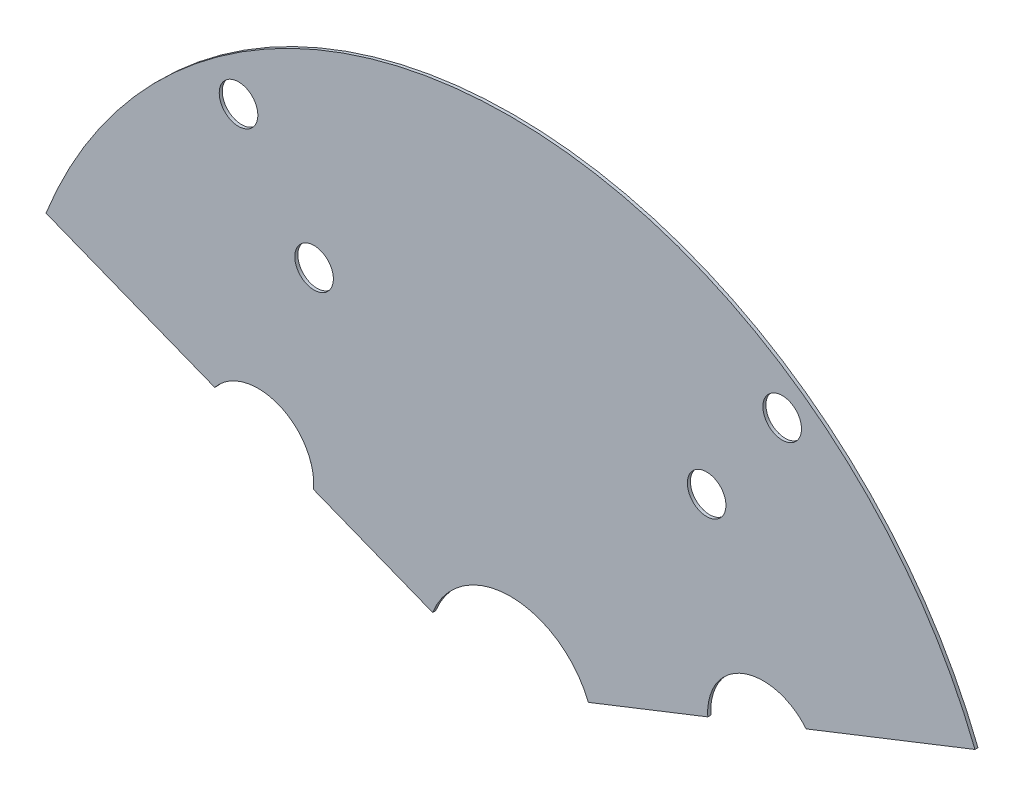
SolidWorks part; units mm, degrees
ref_plane "Front Plane" through (0, 0, 0) normal (0, 0, 1) x (1, 0, 0)
ref_plane "Top Plane" through (0, 0, 0) normal (0, 1, 0) x (1, 0, 0)
ref_plane "Right Plane" through (0, 0, 0) normal (1, 0, 0) x (0, 0, -1)
sketch "Sketch1" plane through (0, 0, 0) normal (0, 0, 1) x (1, 0, 0)
  line L0 (-25.2075, 29.5777) -> (-20.3405, 33.1137)
  line L1 (-22.774, 31.3457) -> (0, 0) construction
  line L2 (0, 0) -> (-50.8, 0) construction
  circle A0 centre (0, 0) radius 50.8
  circle A1 centre (0, 0) radius 38.862 construction
  circle A12 centre (0, 0) radius 19.05 construction
  circle A19 centre (-38.862, 0) radius 9.1764
  circle A20 centre (0, 0) radius 9.7536
  circle A22 centre (-31.44, 22.8425) radius 9.1764
  circle A23 centre (-12.009, 36.96) radius 9.1764
  circle A24 centre (12.009, 36.96) radius 9.1764
  circle A25 centre (31.44, 22.8425) radius 9.1764
  circle A26 centre (38.862, 0) radius 9.1764
  circle A27 centre (31.44, -22.8425) radius 9.1764
  circle A28 centre (12.009, -36.96) radius 9.1764
  circle A29 centre (-12.009, -36.96) radius 9.1764
  circle A30 centre (-31.44, -22.8425) radius 9.1764
  circle A31 centre (-11.1973, 15.4118) radius 9.2964
  circle A32 centre (11.1973, 15.4118) radius 9.2964
  circle A33 centre (18.1176, -5.8868) radius 9.2964
  circle A34 centre (0, -19.05) radius 9.2964
  circle A35 centre (-18.1176, -5.8868) radius 9.2964
  point P27 (0, 0)
  point P32 (0, 0)
  point P43 (0, 0)
  point P49 (0, 0)
  dimension "D1" = 101.6
  dimension "D2" = 11.938
  dimension "D3" = 18.5928
  dimension "D4" = 38.1
  dimension "D5" = 10
  dimension "D6" = 5
sketch "Sketch2" plane through (0, 0, 0) normal (0, 0, 1) x (1, 0, 0)
  circle A0 centre (0, 0) radius 50.165
  circle A1 centre (0, -19.05) radius 9.2964 construction
  circle A2 centre (18.1176, -5.8868) radius 9.2964 construction
  circle A3 centre (11.1973, 15.4118) radius 9.2964 construction
  circle A4 centre (-11.1973, 15.4118) radius 9.2964 construction
  circle A5 centre (-18.1176, -5.8868) radius 9.2964 construction
  circle A6 centre (-38.862, 0) radius 9.1764 construction
  circle A7 centre (-31.44, -22.8425) radius 9.1764 construction
  circle A8 centre (-12.009, -36.96) radius 9.1764 construction
  circle A9 centre (12.009, -36.96) radius 9.1764 construction
  circle A10 centre (31.44, -22.8425) radius 9.1764 construction
  circle A11 centre (38.862, 0) radius 9.1764 construction
  circle A12 centre (31.44, 22.8425) radius 9.1764 construction
  circle A13 centre (12.009, 36.96) radius 9.1764 construction
  circle A14 centre (-12.009, 36.96) radius 9.1764 construction
  circle A15 centre (-31.44, 22.8425) radius 9.1764 construction
  circle A17 centre (0, 0) radius 7.62
  circle A18 centre (0, -19.05) radius 9.2964
  circle A19 centre (18.1176, -5.8868) radius 9.2964
  circle A20 centre (11.1973, 15.4118) radius 9.2964
  circle A21 centre (-11.1973, 15.4118) radius 9.2964
  circle A22 centre (-18.1176, -5.8868) radius 9.2964
  circle A23 centre (-38.862, 0) radius 9.1764
  circle A24 centre (-31.44, -22.8425) radius 9.1764
  circle A25 centre (-12.009, -36.96) radius 9.1764
  circle A26 centre (12.009, -36.96) radius 9.1764
  circle A27 centre (31.44, -22.8425) radius 9.1764
  circle A28 centre (38.862, 0) radius 9.1764
  circle A29 centre (31.44, 22.8425) radius 9.1764
  circle A30 centre (12.009, 36.96) radius 9.1764
  circle A31 centre (-12.009, 36.96) radius 9.1764
  circle A32 centre (-31.44, 22.8425) radius 9.1764
  dimension "D1" = 15.24
  dimension "D2" = 100.33
sketch "Sketch4" plane through (0, 0, 0) normal (0, 0, 1) x (1, 0, 0)
  line L0 (-38.862, 0) -> (-31.44, 22.8425) construction
  line L1 (-11.1973, 15.4118) -> (-18.1176, -5.8868) construction
  line L3 (-2.8326, 36.96) -> (0, 36.96) construction
  line L4 (0, 15.4118) -> (-1.9009, 15.4118) construction
  line L8 (0, 0) -> (0, 50.165) construction
  line L10 (-0.5081, 8.2393) -> (-3.0331, 49.1826)
  line L13 (-28.9637, 39.8651) -> (0, 0) construction
  line L14 (-7.6791, 3.0294) -> (-45.8381, 18.0829)
  arc A3 (-3.0331, 49.1826) -> (-45.8381, 18.0829) centre (0, 0) ccw
  circle A6 centre (-11.1973, 15.4118) radius 9.2964 construction
  circle A7 centre (-12.009, 36.96) radius 9.1764 construction
  circle A8 centre (-31.44, 22.8425) radius 9.1764 construction
  circle A13 centre (-11.1973, 15.4118) radius 9.2964 construction
  circle A14 centre (-12.009, 36.96) radius 9.1764 construction
  circle A15 centre (-31.44, 22.8425) radius 9.1764 construction
  arc A16 (-0.5081, 8.2393) -> (-7.6791, 3.0294) centre (0, 0) ccw
  circle A18 centre (0, 0) radius 50.165 construction
  point P5 (-0.9505, 15.4118)
  point P6 (-1.4163, 36.96)
  dimension "D1" = 8.255
  dimension "D2" = 49.276
  dimension "D3" = 15.4118
  dimension "D4" = 36.96
  dimension "D5" = 28.9637
  dimension "D6" = 39.8651
sketch "Sketch5" plane through (0, 0, 0) normal (0, 0, 1) x (1, 0, 0)
  line L0 (-7.6791, 3.0294) -> (-45.8381, 18.0829) construction
  line L1 (-7.6791, 3.0294) -> (-45.8381, 18.0829)
  line L2 (0, 0) -> (0, 65.0047) construction
  line L3 (7.6791, 3.0294) -> (45.8381, 18.0829)
  arc A0 (-0.5081, 8.2393) -> (-7.6791, 3.0294) centre (0, 0) ccw construction
  arc A1 (-3.0331, 49.1826) -> (-45.8381, 18.0829) centre (0, 0) ccw construction
  arc A2 (-0.5081, 8.2393) -> (-7.6791, 3.0294) centre (0, 0) ccw
  arc A3 (-3.0331, 49.1826) -> (-45.8381, 18.0829) centre (0, 0) ccw
  arc A4 (-0.5081, 8.2393) -> (7.6791, 3.0294) centre (0, 0) cw
  arc A5 (-3.0331, 49.1826) -> (45.8381, 18.0829) centre (0, 0) cw
extrude "Boss-Extrude1" add sketch "Sketch5" along normal blind 0.3
sketch "Sketch6" plane through (0, 0, 0.3) normal (0, 0, 1) x (1, 0, 0)
  line L0 (-12.009, 27.7835) -> (-12.009, 24.6727) construction
  line L1 (-12.009, 26.2281) -> (0, 26.2281) construction
  line L2 (0, 0) -> (0, 50.165) construction
  circle A0 centre (-12.009, 36.96) radius 9.1764 construction
  circle A1 centre (-11.1973, 15.4118) radius 9.2964 construction
  circle A2 centre (0, 26.2281) radius 3.175
  circle A3 centre (24.9444, 8.1049) radius 3.175
  circle A4 centre (15.4165, -21.219) radius 3.175
  circle A5 centre (-15.4165, -21.219) radius 3.175
  circle A6 centre (-24.9444, 8.1049) radius 3.175
  point P21 (0, 0)
  dimension "D1" = 6.35
  dimension "D2" = 5
sketch "Sketch7" plane through (0, 0, 0) normal (0, 0, -1) x (-1, 0, 0)
  circle A0 centre (-26.8139, 36.9192) radius 1.905
  circle A1 centre (-19.3586, 26.6579) radius 1.905
  circle A2 centre (26.8388, 36.901) radius 1.905
  circle A3 centre (19.3836, 26.6397) radius 1.905
extrude "Cut-Extrude2" cut sketch "Sketch7" against normal through all
sketch "Sketch8" plane through (0, 0, 0) normal (0, 0, -1) x (-1, 0, 0)
  line L0 (-7.6791, 3.0294) -> (-45.8381, 18.0829) construction
  line L1 (45.8381, 18.0829) -> (7.6791, 3.0294) construction
  line L2 (-19.4682, 7.6801) -> (-29.1791, 11.511)
  line L3 (29.1834, 11.5127) -> (19.4255, 7.6633)
  arc A0 (29.1834, 11.5127) -> (19.4255, 7.6633) centre (24.8958, 8.0891) ccw
  arc A1 (-19.4682, 7.6801) -> (-29.1791, 11.511) centre (-24.9444, 8.0222) ccw
  dimension "D1" = 5.4868
extrude "Cut-Extrude3" cut sketch "Sketch8" against normal through all
